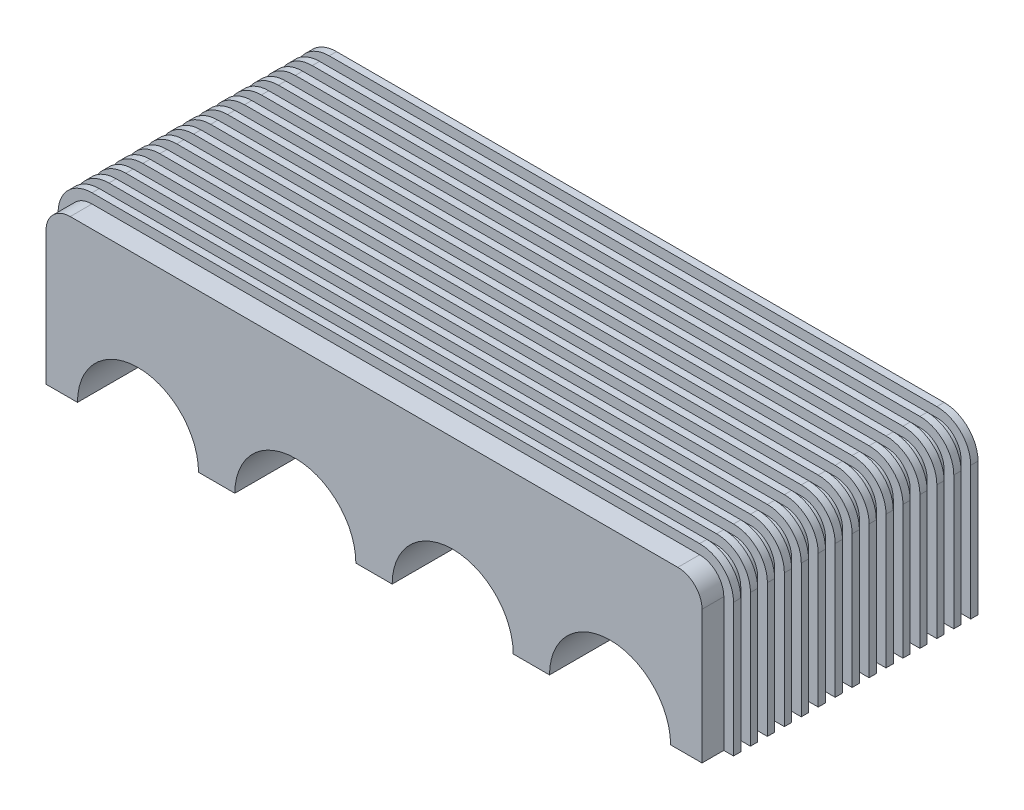
SolidWorks part; units mm, degrees
ref_plane "Front Plane" through (0, 0, 0) normal (0, 0, 1) x (1, 0, 0)
ref_plane "Top Plane" through (0, 0, 0) normal (0, 1, 0) x (1, 0, 0)
ref_plane "Right Plane" through (0, 0, 0) normal (1, 0, 0) x (0, 0, -1)
sketch "Sketch1" plane through (0, 0, 0) normal (0, 0, 1) x (1, 0, 0)
  line L0 (135.5, 65) -> (135.5, 0) construction
  line L1 (128, 0) -> (143, 0)
  line L2 (0, 0) -> (0, 55)
  line L3 (10, 65) -> (261, 65)
  line L4 (271, 0) -> (271, 55)
  line L5 (258, 0) -> (271, 0)
  line L6 (193, 0) -> (208, 0)
  line L7 (13, 0) -> (0, 0)
  line L8 (78, 0) -> (63, 0)
  arc A0 (261, 65) -> (271, 55) centre (261, 55) cw
  arc A1 (0, 55) -> (10, 65) centre (10, 55) cw
  arc A2 (258, 0) -> (208, 0) centre (233, 0) ccw
  arc A3 (193, 0) -> (143, 0) centre (168, 0) ccw
  arc A4 (78, 0) -> (128, 0) centre (103, 0) cw
  arc A5 (13, 0) -> (63, 0) centre (38, 0) cw
  dimension "D1" = 10
  dimension "D4" = 25
  dimension "D6" = 50
  dimension "D2" = 271
  dimension "D3" = 65
  dimension "D5" = 13
  dimension "D7" = 15
extrude "Boss-Extrude1" add sketch "Sketch1" along normal blind 110
sketch "Sketch2" plane through (0, 0, 0) normal (0, 0, -1) x (-1, 0, 0)
  line L0 (4, 0) -> (4, 55)
  line L1 (-10, 69) -> (-261, 69)
  line L2 (-275, 55) -> (-275, 0)
  line L3 (-271, 0) -> (-275, 0)
  line L4 (4, 0) -> (0, 0)
  line L8 (-13, 0) -> (0, 0)
  line L9 (0, 0) -> (0, 55)
  line L10 (-10, 65) -> (-261, 65)
  line L11 (-271, 55) -> (-271, 0)
  line L12 (-271, 0) -> (-258, 0)
  line L13 (-208, 0) -> (-193, 0)
  line L14 (-143, 0) -> (-128, 0)
  line L15 (-78, 0) -> (-63, 0)
  line L17 (0, 0) -> (0, 55)
  line L18 (-10, 65) -> (-261, 65)
  line L19 (-271, 55) -> (-271, 0)
  arc A0 (4, 55) -> (-10, 69) centre (-10, 55) ccw
  arc A1 (-261, 69) -> (-275, 55) centre (-261, 55) ccw
  arc A6 (0, 55) -> (-10, 65) centre (-10, 55) ccw
  arc A7 (-261, 65) -> (-271, 55) centre (-261, 55) ccw
  arc A8 (-208, 0) -> (-258, 0) centre (-233, 0) ccw
  arc A9 (-143, 0) -> (-193, 0) centre (-168, 0) ccw
  arc A10 (-78, 0) -> (-128, 0) centre (-103, 0) ccw
  arc A11 (-13, 0) -> (-63, 0) centre (-38, 0) ccw
  arc A12 (0, 55) -> (-10, 65) centre (-10, 55) ccw
  arc A13 (-261, 65) -> (-271, 55) centre (-261, 55) ccw
  dimension "D1" = 0
  dimension "D2" = 4
extrude "Boss-Extrude3" add sketch "Sketch2" against normal blind 3 separate body
pattern_linear "LPattern1" count 15 spacing 7 along (0, 0, 1) of "Boss-Extrude3"
